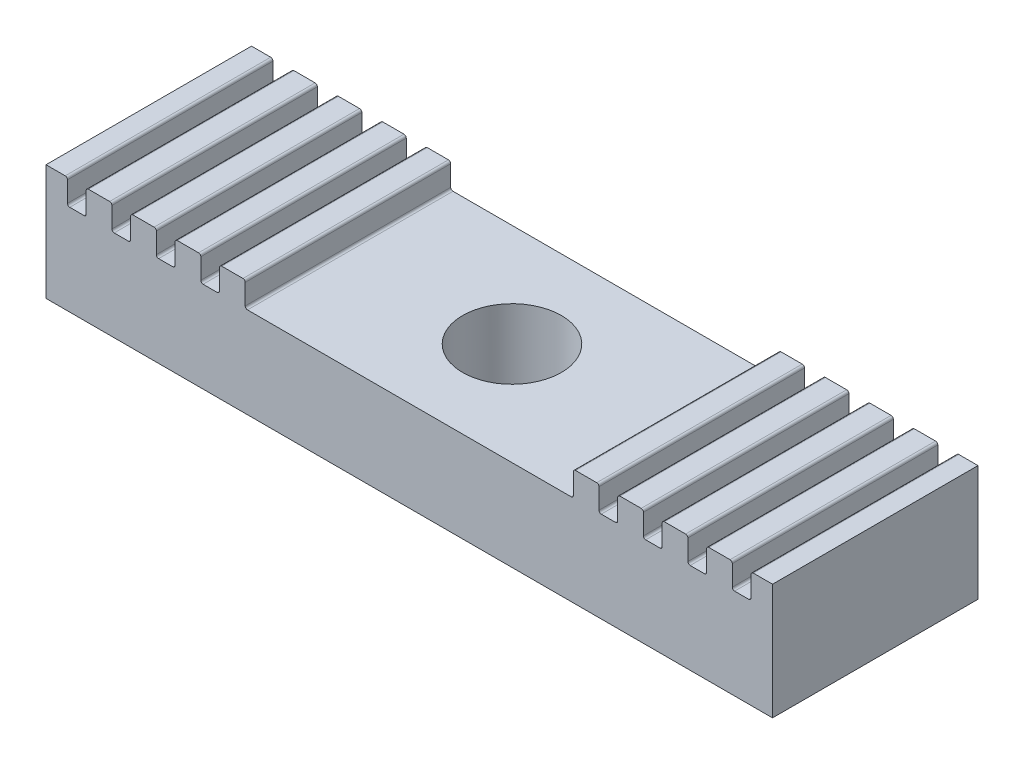
SolidWorks part; units mm, degrees
material "7075-T6, Plate (SS)"
ref_plane "Front" through (0, 0, 0) normal (0, 0, 1) x (1, 0, 0)
ref_plane "Top" through (0, 0, 0) normal (0, 1, 0) x (1, 0, 0)
ref_plane "Right" through (0, 0, 0) normal (1, 0, 0) x (0, 0, -1)
sketch "Sketch1" plane through (0, 0, 0) normal (0, 1, 0) x (1, 0, 0)
  line L0 (0, 4.525) -> (0, 0)
  line L1 (-20.1, 4.525) -> (20.1, 4.525)
  line L2 (-20.1, 4.525) -> (-20.1, -4.525)
  line L3 (-20.1, -4.525) -> (20.1, -4.525)
  line L4 (20.1, 4.525) -> (20.1, -4.525)
  line L5 (0, 0) -> (20.1, 0) construction
  line L6 (0, 0) -> (0, -4.525)
  circle A0 centre (0, 0) radius 2.175
  dimension "D3" = 4.35
  dimension "D1" = 40.2
  dimension "D2" = 9.05
extrude "Boss-Extrude1" add sketch "Sketch1" along normal blind 5.1 contours A0 L5 L4 L1 L0 | L5 A0 L6 L3 L4
sketch "Sketch2" plane through (0, 0, 4.525) normal (0, 0, 1) x (1, 0, 0)
  line L0 (0, 5.1) -> (20.1, 5.1) construction
  line L1 (-7.225, 5.1) -> (7.225, 5.1)
  line L2 (-7.225, 5.1) -> (-7.225, 4)
  line L3 (-7.225, 4) -> (7.225, 4)
  line L4 (7.225, 5.1) -> (7.225, 4)
  line L5 (0, 0) -> (0, 4) construction
  dimension "D1" = 14.45
  dimension "D2" = 4
extrude "Cut-Extrude1" cut sketch "Sketch2" against normal through all
sketch "Sketch3" plane through (0, 0, 4.525) normal (0, 0, 1) x (1, 0, 0)
  line L1 (8.3571, 5.1) -> (9.1821, 5.1)
  line L2 (8.3571, 5.1) -> (8.3571, 4)
  line L3 (8.3571, 4) -> (9.1821, 4)
  line L4 (9.1821, 5.1) -> (9.1821, 4)
  line L6 (10.3143, 5.1) -> (11.1393, 5.1)
  line L7 (10.3143, 5.1) -> (10.3143, 4)
  line L8 (10.3143, 4) -> (11.1393, 4)
  line L9 (11.1393, 5.1) -> (11.1393, 4)
  line L10 (12.2714, 5.1) -> (13.0964, 5.1)
  line L11 (12.2714, 5.1) -> (12.2714, 4)
  line L12 (12.2714, 4) -> (13.0964, 4)
  line L13 (13.0964, 5.1) -> (13.0964, 4)
  line L14 (14.2286, 5.1) -> (15.0536, 5.1)
  line L15 (14.2286, 5.1) -> (14.2286, 4)
  line L16 (14.2286, 4) -> (15.0536, 4)
  line L17 (15.0536, 5.1) -> (15.0536, 4)
  line L18 (16.1857, 5.1) -> (17.0107, 5.1)
  line L19 (16.1857, 5.1) -> (16.1857, 4)
  line L20 (16.1857, 4) -> (17.0107, 4)
  line L21 (17.0107, 5.1) -> (17.0107, 4)
  line L22 (18.1429, 5.1) -> (18.9679, 5.1)
  line L23 (18.1429, 5.1) -> (18.1429, 4)
  line L24 (18.1429, 4) -> (18.9679, 4)
  line L25 (18.9679, 5.1) -> (18.9679, 4)
  line L26 (0, 4) -> (7.225, 4) construction
  line L27 (7.225, 4) -> (8.3571, 4) construction
  line L28 (9.1821, 4) -> (10.3143, 4) construction
  line L29 (11.1393, 4) -> (12.2714, 4) construction
  line L30 (13.0964, 4) -> (14.2286, 4) construction
  line L31 (15.0536, 4) -> (16.1857, 4) construction
  line L32 (17.0107, 4) -> (18.1429, 4) construction
  line L33 (18.9679, 4) -> (20.1, 4) construction
  line L34 (20.1, 5.1) -> (20.1, 0) construction
  line L35 (7.225, 5.1) -> (20.1, 5.1) construction
  dimension "D1" = 0.825
extrude "Cut-Extrude2" cut sketch "Sketch3" against normal blind 10
fillet "Fillet1" radius 0.1 27 edges at (17.0107, 4, 0) (15.0536, 4, 0) (13.0964, 4, 0) (11.1393, 4, 0) (9.1821, 4, 0) (7.225, 4, 0) (18.1429, 4, 0) (16.1857, 4, 0) (14.2286, 4, 0) (12.2714, 4, 0) (10.3143, 4, 0) (8.3571, 4, 0) (18.9679, 4, 0) (7.225, 5.1, 0) (8.3571, 5.1, 0) (9.1821, 5.1, 0) (10.3143, 5.1, 0) (11.1393, 5.1, 0) (12.2714, 5.1, 0) (13.0964, 5.1, 0) (14.2286, 5.1, 0) (15.0536, 5.1, 0) (16.1857, 5.1, 0) (17.0107, 5.1, 0) (18.1429, 5.1, 0) (18.9679, 5.1, 0) (20.1, 5.1, 0)
mirror "Mirror3" about plane through (0, 5.1, 0) normal (1, 0, 0) of bodies 103
sketch "Sketch4" plane through (0, 0, 4.525) normal (0, 0, 1) x (1, 0, 0)
  line L1 (16, 5.1) -> (20.1, 5.1)
  line L2 (16, 5.1) -> (16, 0)
  line L3 (16, 0) -> (20.1, 0)
  line L4 (20.1, 5.1) -> (20.1, 0)
  line L5 (19.0679, 5.1) -> (20, 5.1) construction
  line L6 (0, 0) -> (0, 8.1956) construction
  line L7 (-20.1, 5.1) -> (-20.1, 0)
  line L8 (-16, 0) -> (-20.1, 0)
  line L9 (-16, 5.1) -> (-16, 0)
  line L10 (-16, 5.1) -> (-20.1, 5.1)
  dimension "D1" = 32
extrude "Cut-Extrude3" cut sketch "Sketch4" against normal blind 10
